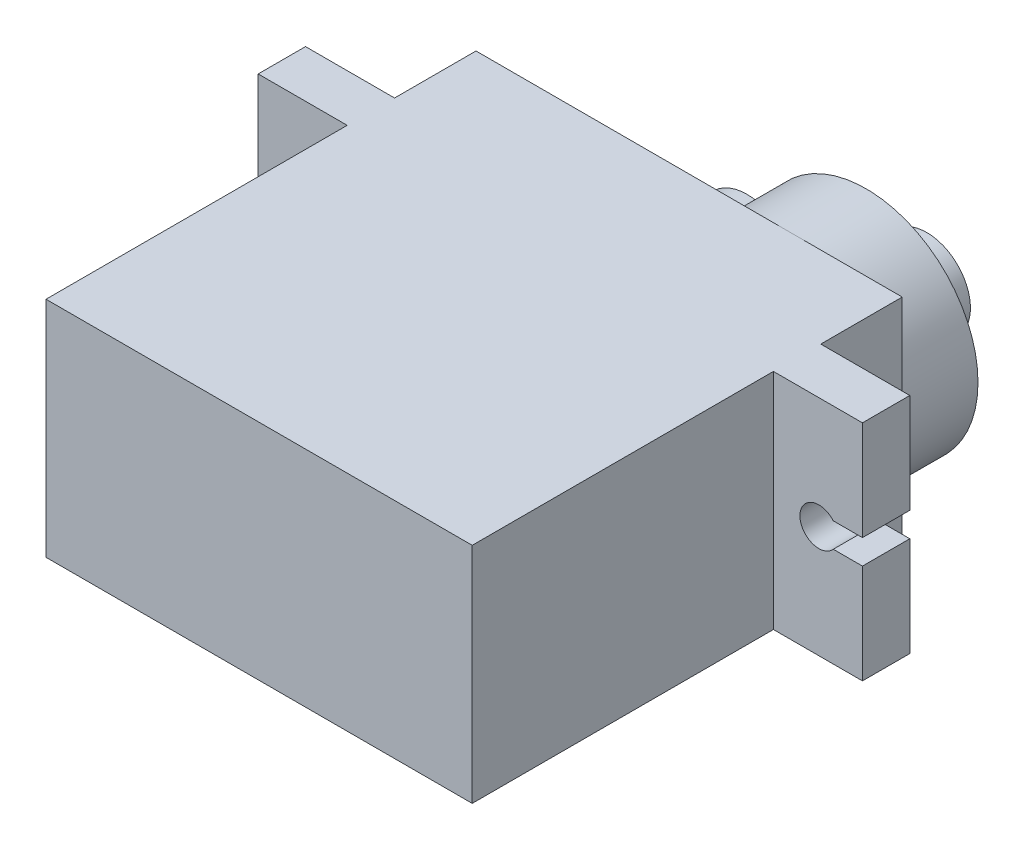
SolidWorks part; units mm, degrees
ref_plane "Front Plane" through (0, 0, 0) normal (0, 0, 1) x (1, 0, 0)
ref_plane "Top Plane" through (0, 0, 0) normal (0, 1, 0) x (1, 0, 0)
ref_plane "Right Plane" through (0, 0, 0) normal (1, 0, 0) x (0, 0, -1)
sketch "Sketch1" plane through (0, 0, 0) normal (0, 1, 0) x (1, 0, 0)
  line L1 (0, 0) -> (22.5, 0)
  line L2 (0, 0) -> (0, 22.7)
  line L3 (0, 22.7) -> (22.5, 22.7)
  line L4 (22.5, 0) -> (22.5, 22.7)
  dimension "D1" = 22.5
  dimension "D2" = 22.7
extrude "Boss-Extrude1" add sketch "Sketch1" along normal blind 11.8
sketch "Sketch2" plane through (0, 11.8, 0) normal (0, 1, 0) x (1, 0, 0)
  line L0 (0, 0) -> (22.5, 0) construction
  line L1 (-4.7, 18.4) -> (27.2, 18.4)
  line L2 (-4.7, 18.4) -> (-4.7, 15.9)
  line L3 (-4.7, 15.9) -> (27.2, 15.9)
  line L4 (27.2, 18.4) -> (27.2, 15.9)
  line L5 (22.5, 0) -> (22.5, 22.7) construction
  line L6 (0, 22.7) -> (0, 0) construction
  dimension "D1" = 15.9
  dimension "D2" = 2.5
  dimension "D3" = 4.7
  dimension "D4" = 4.7
extrude "Boss-Extrude2" add sketch "Sketch2" against normal blind 11.8
sketch "Sketch3" plane through (0, 0, -22.7) normal (0, 0, -1) x (-1, 0, 0)
  line L0 (-16.6, 5.9) -> (-7.8, 5.9) construction
  arc A0 (-11.1833, 8.2387) -> (-11.1833, 3.5613) centre (-16.6, 5.9) ccw
  arc A1 (-11.1833, 3.5613) -> (-11.1833, 8.2387) centre (-10.3, 5.9) ccw
  dimension "D2" = 5
  dimension "D1" = 8.8
extrude "Boss-Extrude3" add sketch "Sketch3" along normal blind 4
sketch "Sketch4" plane through (0, 0, -26.7) normal (0, 0, -1) x (-1, 0, 0)
  circle A0 centre (-16.6, 5.9) radius 2.3
  dimension "D1" = 4.6
extrude "Boss-Extrude4" add sketch "Sketch4" along normal blind 3.2
sketch "Sketch5" plane through (0, 0, -18.4) normal (0, 0, -1) x (-1, 0, 0)
  line L0 (-27.2, 5.9) -> (4.7, 5.9) construction
  line L1 (-27.2, 0) -> (-27.2, 11.8) construction
  line L2 (4.7, 0) -> (4.7, 11.8) construction
  line L3 (-27.2, 5.25) -> (-27.2, 6.55)
  line L4 (-27.2, 6.55) -> (-25.6599, 6.55)
  line L5 (-27.2, 5.25) -> (-25.6599, 5.25)
  line L6 (-11.25, 5.9) -> (-11.25, 11.8) construction
  line L7 (-16.6, 11.8) -> (0, 11.8) construction
  line L8 (4.7, 5.25) -> (3.1599, 5.25)
  line L9 (4.7, 6.55) -> (3.1599, 6.55)
  line L10 (4.7, 5.25) -> (4.7, 6.55)
  arc A0 (-25.6599, 5.25) -> (-25.6599, 6.55) centre (-24.9, 5.9) ccw
  arc A1 (3.1599, 5.25) -> (3.1599, 6.55) centre (2.4, 5.9) cw
  dimension "D1" = 2
  dimension "D2" = 2.3
  dimension "D3" = 0.65
extrude "Cut-Extrude1" cut sketch "Sketch5" against normal blind 3.2
